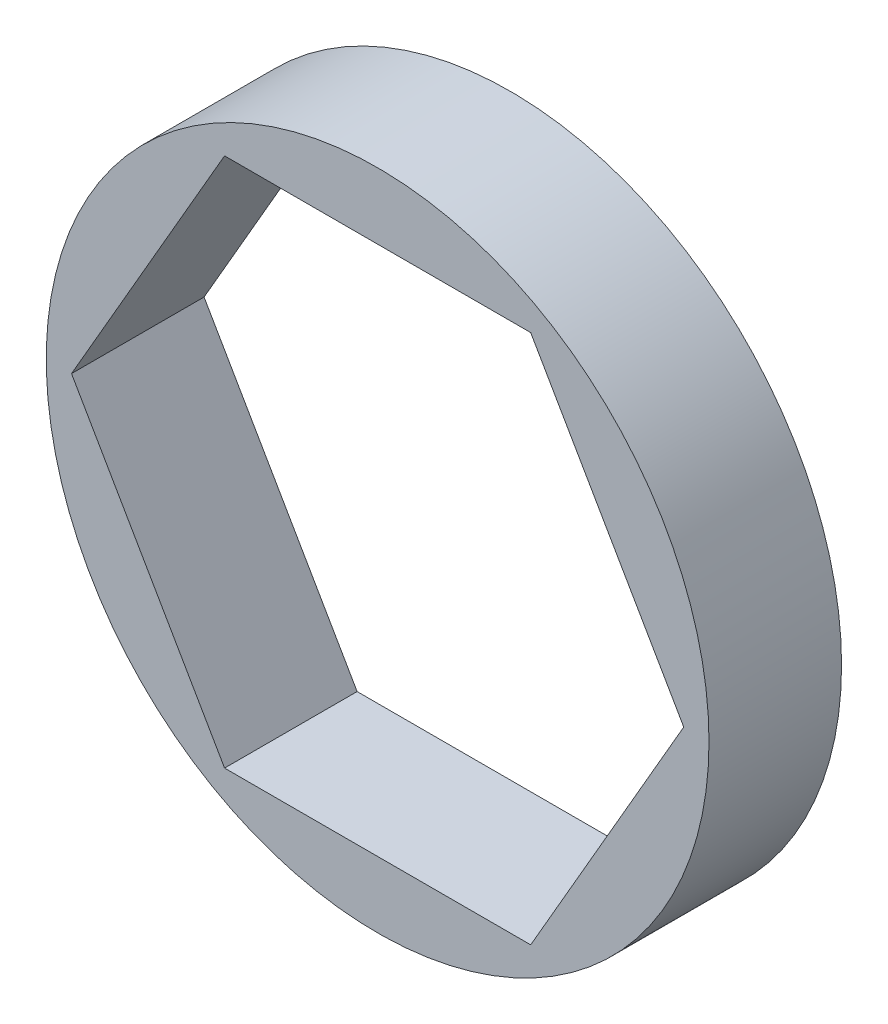
SolidWorks part; units mm, degrees
material "ABS"
ref_plane "Front Plane" through (0, 0, 0) normal (0, 0, 1) x (1, 0, 0)
ref_plane "Top Plane" through (0, 0, 0) normal (0, 1, 0) x (1, 0, 0)
ref_plane "Right Plane" through (0, 0, 0) normal (1, 0, 0) x (0, 0, -1)
sketch "Sketch1" plane through (0, 0, 0) normal (0, 0, 1) x (1, 0, 0)
  line L1 (-3.6662, -6.35) -> (3.6662, -6.35)
  line L2 (3.6662, -6.35) -> (7.3323, 0)
  line L3 (7.3323, 0) -> (3.6662, 6.35)
  line L4 (3.6662, 6.35) -> (-3.6662, 6.35)
  line L5 (-3.6662, 6.35) -> (-7.3323, 0)
  line L6 (-7.3323, 0) -> (-3.6662, -6.35)
  circle A0 centre (0, 0) radius 6.35 construction
  circle A1 centre (0, 0) radius 7.9375
  dimension "D1" = 12.7
  dimension "D2" = 15.875
extrude "Boss-Extrude1" add sketch "Sketch1" along normal blind 3.175
